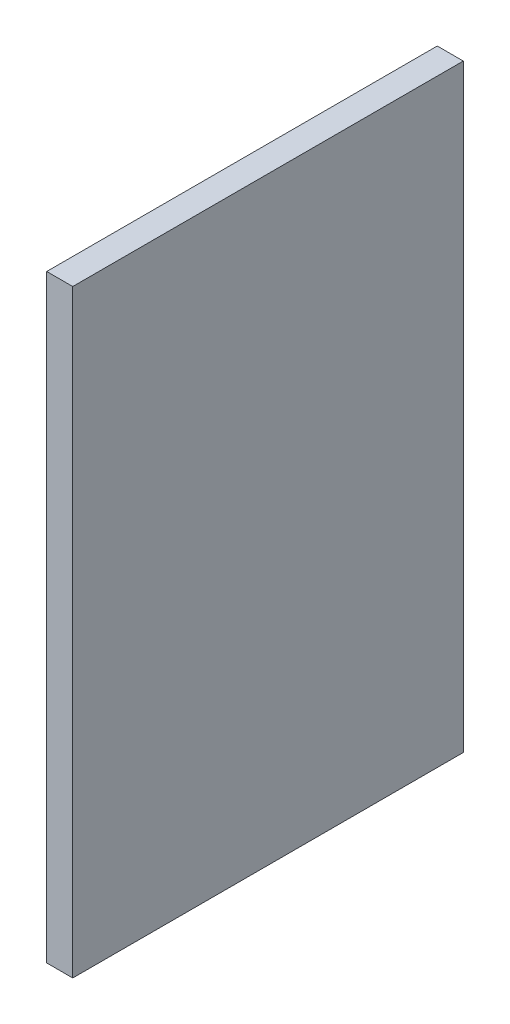
SolidWorks part; units mm, degrees
ref_plane "Front Plane" through (0, 0, 0) normal (0, 0, 1) x (1, 0, 0)
ref_plane "Top Plane" through (0, 0, 0) normal (0, 1, 0) x (1, 0, 0)
ref_plane "Right Plane" through (0, 0, 0) normal (1, 0, 0) x (0, 0, -1)
sketch "Sketch1" plane through (0, 0, 0) normal (0, 1, 0) x (1, 0, 0)
  line L1 (0, 0) -> (12.7, 0)
  line L2 (0, 0) -> (0, 190.5)
  line L3 (0, 190.5) -> (12.7, 190.5)
  line L4 (12.7, 0) -> (12.7, 190.5)
  dimension "D1" = 190.5
  dimension "D2" = 12.7
extrude "Boss-Extrude1" add sketch "Sketch1" along normal blind 292.1
